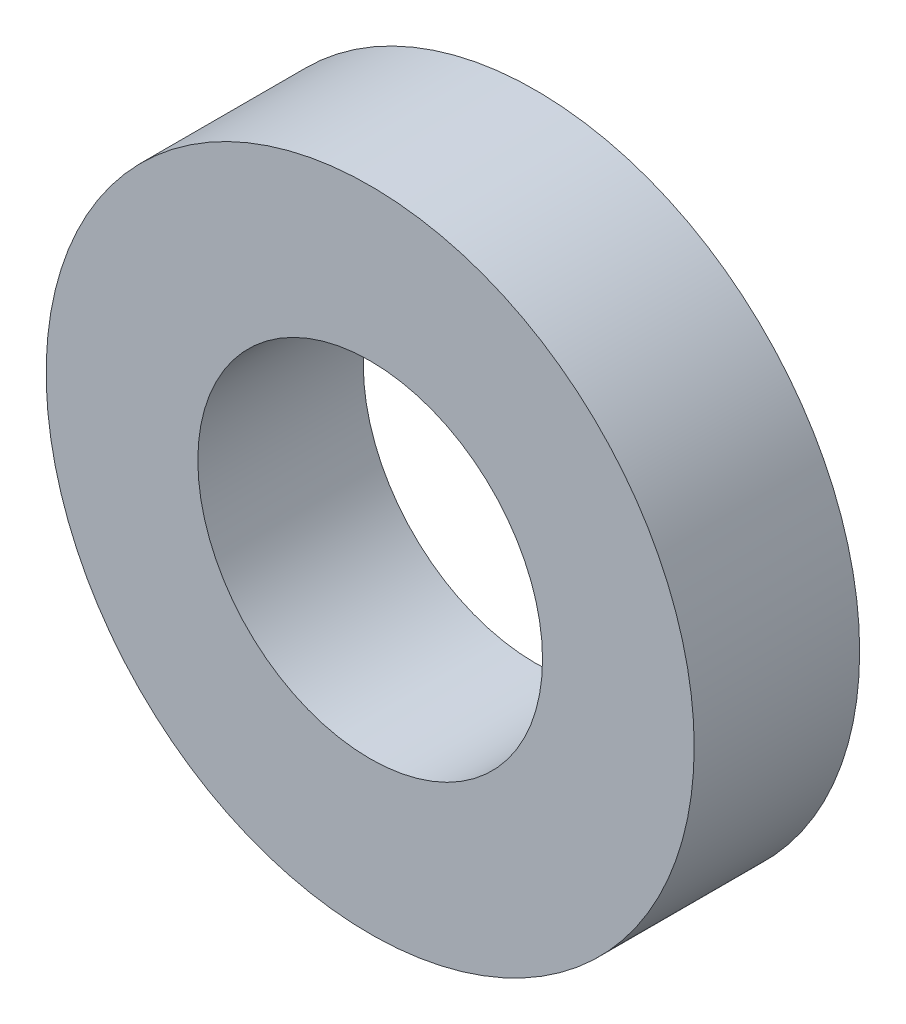
SolidWorks part; units mm, degrees
ref_plane "Front Plane" through (0, 0, 0) normal (0, 0, 1) x (1, 0, 0)
ref_plane "Top Plane" through (0, 0, 0) normal (0, 1, 0) x (1, 0, 0)
ref_plane "Right Plane" through (0, 0, 0) normal (1, 0, 0) x (0, 0, -1)
sketch "Sketch1" plane through (0, 0, 0) normal (0, 0, 1) x (1, 0, 0)
  circle A0 centre (0, 0) radius 23.5
  circle A1 centre (0, 0) radius 12.5
  dimension "D1" = 25
  dimension "D2" = 47
extrude "Boss-Extrude1" add sketch "Sketch1" along normal blind 12
